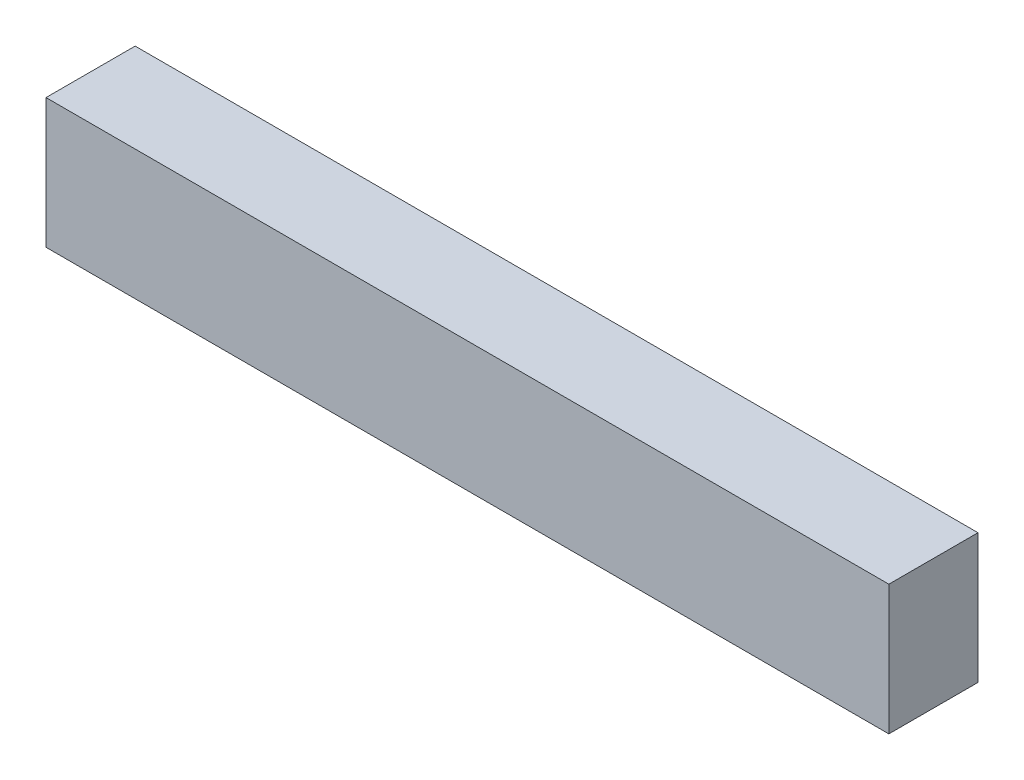
SolidWorks part; units mm, degrees
ref_plane "前视基准面" through (0, 0, 0) normal (0, 0, 1) x (1, 0, 0)
ref_plane "上视基准面" through (0, 0, 0) normal (0, 1, 0) x (1, 0, 0)
ref_plane "右视基准面" through (0, 0, 0) normal (1, 0, 0) x (0, 0, -1)
other "Configuration Table"
sketch "草图1" plane through (0, 0, 0) normal (0, 0, 1) x (1, 0, 0)
  line L1 (-260, -40) -> (260, -40)
  line L2 (-260, -40) -> (-260, 40)
  line L3 (-260, 40) -> (260, 40)
  line L4 (260, -40) -> (260, 40)
  line L5 (-260, -40) -> (260, 40) construction
  line L6 (-260, 40) -> (260, -40) construction
  point P0 (0, 0)
extrude "凸台-拉伸1" add sketch "草图1" along normal blind 55
